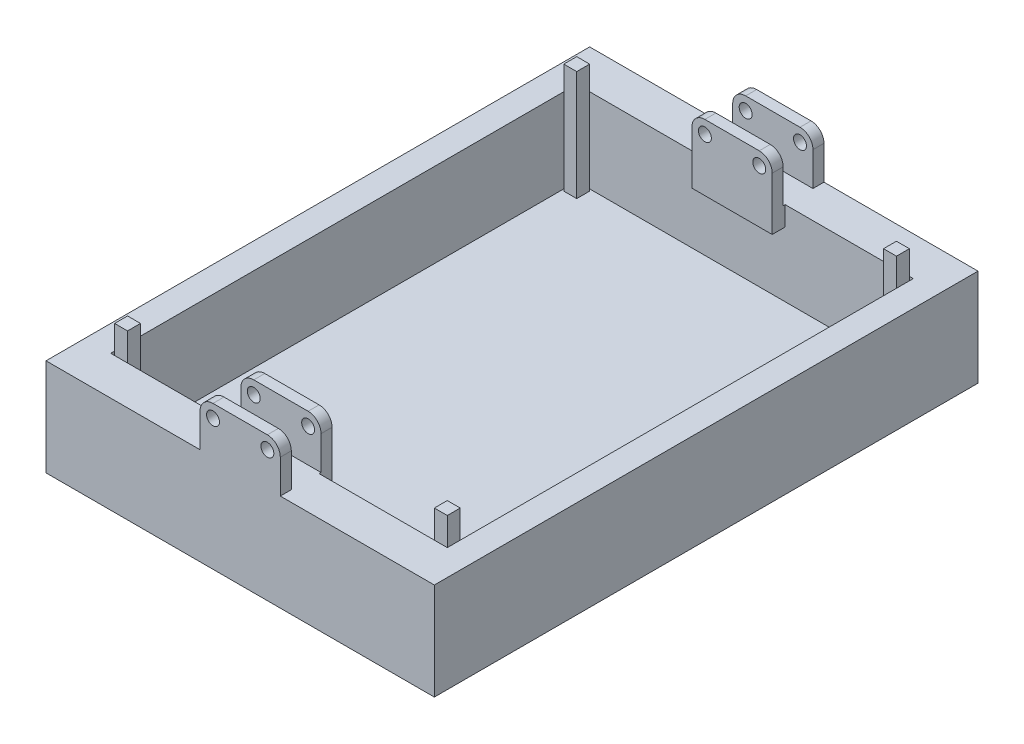
SolidWorks part; units mm, degrees
ref_plane "Front Plane" through (0, 0, 0) normal (0, 0, 1) x (1, 0, 0)
ref_plane "Top Plane" through (0, 0, 0) normal (0, 1, 0) x (1, 0, 0)
ref_plane "Right Plane" through (0, 0, 0) normal (1, 0, 0) x (0, 0, -1)
sketch "Sketch1" plane through (0, 0, 0) normal (0, 1, 0) x (1, 0, 0)
  line L1 (-30, 42) -> (30, 42)
  line L2 (-30, 42) -> (-30, -42)
  line L3 (-30, -42) -> (30, -42)
  line L4 (30, 42) -> (30, -42)
  line L5 (-30, 42) -> (30, -42) construction
  line L6 (-30, -42) -> (30, 42) construction
  point P0 (0, 0)
extrude "Boss-Extrude1" add sketch "Sketch1" along normal blind 9 and the other way blind 6
sketch "Sketch2" plane through (0, 9, 0) normal (0, 1, 0) x (1, 0, 0)
  line L1 (-26, 36) -> (26, 36)
  line L2 (-26, 36) -> (-26, -36)
  line L3 (-26, -36) -> (26, -36)
  line L4 (26, 36) -> (26, -36)
  line L5 (-26, 36) -> (26, -36) construction
  line L6 (-26, -36) -> (26, 36) construction
  point P0 (0, 0)
sketch "Sketch4" plane through (0, 9, 0) normal (0, 1, 0) x (1, 0, 0)
  line L0 (-26, 36) -> (26, 36) construction
  line L1 (-25.7, 35.7) -> (-23.7, 35.7)
  line L2 (-25.7, 35.7) -> (-25.7, 33.7)
  line L3 (-25.7, 33.7) -> (-23.7, 33.7)
  line L4 (-23.7, 35.7) -> (-23.7, 33.7)
  line L5 (-25.7, 35.7) -> (-23.7, 33.7) construction
  line L6 (-25.7, 33.7) -> (-23.7, 35.7) construction
  line L7 (-26, 36) -> (-26, -36) construction
  line L8 (0, -55) -> (0, 55) construction
  line L9 (25.7, 33.7) -> (23.7, 33.7)
  line L10 (23.7, 35.7) -> (23.7, 33.7)
  line L11 (25.7, 35.7) -> (23.7, 35.7)
  line L12 (25.7, 35.7) -> (25.7, 33.7)
  line L13 (-55, 0) -> (55, 0) construction
  line L14 (25.7, -35.7) -> (25.7, -33.7)
  line L15 (25.7, -35.7) -> (23.7, -35.7)
  line L16 (23.7, -35.7) -> (23.7, -33.7)
  line L17 (25.7, -33.7) -> (23.7, -33.7)
  line L18 (-25.7, -33.7) -> (-23.7, -33.7)
  line L19 (-23.7, -35.7) -> (-23.7, -33.7)
  line L20 (-25.7, -35.7) -> (-23.7, -35.7)
  line L21 (-25.7, -35.7) -> (-25.7, -33.7)
  point P0 (-24.7, 34.7)
  dimension "D1" = 0.3
  dimension "D2" = 0.3
extrude "Cut-Extrude2" cut sketch "Sketch2" against normal blind 13
extrude "Boss-Extrude6" add sketch "Sketch4" along normal blind 4 and the other way blind 13
sketch "Sketch7" plane through (0, 0, -42) normal (0, 0, -1) x (-1, 0, 0)
  line L0 (-30, 9) -> (30, 9) construction
  line L1 (0, 10.45) -> (0, -10.45) construction
  line L2 (-6.2, 14.2) -> (-6.2, 9)
  line L3 (-6.2, 9) -> (6.2, 9)
  line L4 (6.2, 9) -> (6.2, 14.2)
  line L5 (-4.2, 16.2) -> (4.2, 16.2)
  circle A0 centre (-4.2, 14.2) radius 1
  circle A1 centre (-4.2, 14.2) radius 2
  circle A2 centre (4.2, 14.2) radius 1
  circle A3 centre (4.2, 14.2) radius 2
  line M5 (30, 9) -> (-30, 9)
  dimension "D1" = 5.2
  dimension "D2" = 4.2
extrude "Boss-Extrude7" add sketch "Sketch7" against normal blind 1.7 contours L4 A3 L5 A1 L2 M5 | A1 A0 | A3 A2
sketch "Sketch8" plane through (0, 0, -36) normal (0, 0, 1) x (1, 0, 0)
  line L1 (-6.2, 9) -> (6.2, 9)
  line L2 (-6.2, 9) -> (-6.2, 6)
  line L3 (-6.2, 6) -> (6.2, 6)
  line L4 (6.2, 9) -> (6.2, 6)
  line L5 (-6.2, 9) -> (6.2, 6) construction
  line L6 (-6.2, 6) -> (6.2, 9) construction
  line L7 (26, 9) -> (-26, 9) construction
  point P0 (0, 7.5)
extrude "Boss-Extrude8" add sketch "Sketch8" along normal blind 2
ref_plane "Plane15" through (0, 0, -38) normal (0, 0, -1) x (-1, 0, 0)
mirror "Mirror2" about plane through (0, 0, -38) normal (0, 0, -1) of "Boss-Extrude7"
mirror "Mirror3" about plane through (0, 0, 0) normal (0, 0, 1) of "Boss-Extrude7", "Boss-Extrude8", "Mirror2"
sketch "Sketch9" plane through (0, -6, 0) normal (0, -1, 0) x (1, 0, 0)
  spline S0 degree 3 poles (0.7137, 34.7755) (1.8785, 34.7254) (2.2488, 34.857) (2.49, 34.5501) knots 56 56 56 56 57 57 57 57
  spline S1 degree 3 poles (-2.0214, 34.749) (-0.9513, 34.8471) (0.7137, 34.7755) (0.7137, 34.7755) knots 55 55 55 55 56 56 56 56
  spline S2 degree 3 poles (-2.4455, 34.5722) (-2.3096, 34.7198) (-2.1092, 34.7409) (-2.0214, 34.749) knots 54 54 54 54 55 55 55 55
  spline S3 degree 3 poles (-2.5869, 34.148) (-2.585, 34.2282) (-2.5802, 34.4261) (-2.4455, 34.5722) knots 53 53 53 53 54 54 54 54
  spline S4 degree 3 poles (-3.0111, 31.6383) (-2.6923, 31.943) (-2.6271, 32.5207) (-2.5869, 34.148) knots 52 52 52 52 53 53 53 53
  spline S5 degree 3 poles (-3.3469, 31.4439) (-3.1748, 31.4999) (-3.0708, 31.5813) (-3.0111, 31.6383) knots 51 51 51 51 52 52 52 52
  spline S6 degree 3 poles (-4.0848, 31.2495) (-3.8538, 31.3104) (-3.5674, 31.3859) (-3.3469, 31.4439) knots 50 50 50 50 51 51 51 51
  spline S7 degree 3 poles (-5.026, 31.002) (-4.7166, 31.0995) (-4.3985, 31.1667) (-4.0848, 31.2495) knots 49 49 49 49 50 50 50 50
  spline S8 degree 3 poles (-5.7912, 30.8076) (-5.5836, 30.7802) (-5.4979, 30.8532) (-5.026, 31.002) knots 48 48 48 48 49 49 49 49
  spline S9 degree 3 poles (-6.3692, 31.1257) (-6.1058, 30.8983) (-5.9496, 30.8285) (-5.7912, 30.8076) knots 47 47 47 47 48 48 48 48
  spline S10 degree 3 poles (-7.7125, 32.6634) (-7.0924, 32.0321) (-6.9176, 31.5992) (-6.3692, 31.1257) knots 46 46 46 46 47 47 47 47
  spline S11 degree 3 poles (-8.225, 32.9462) (-7.9913, 32.9396) (-7.8194, 32.7722) (-7.7125, 32.6634) knots 45 45 45 45 46 46 46 46
  spline S12 degree 3 poles (-8.6669, 32.7694) (-8.6059, 32.8177) (-8.4413, 32.9522) (-8.225, 32.9462) knots 44 44 44 44 45 45 45 45
  spline S13 degree 3 poles (-11.919, 30.5778) (-10.8645, 31.5186) (-9.2962, 32.2723) (-8.6669, 32.7694) knots 43 43 43 43 44 44 44 44
  spline S14 degree 3 poles (-12.1487, 30.2067) (-12.1074, 30.3969) (-11.982, 30.5216) (-11.919, 30.5778) knots 42 42 42 42 43 43 43 43
  spline S15 degree 3 poles (-11.9057, 29.4599) (-12.0986, 29.7866) (-12.1977, 29.9809) (-12.1487, 30.2067) knots 41 41 41 41 42 42 42 42
  spline S16 degree 3 poles (-11.0352, 28.015) (-11.137, 28.1577) (-11.3933, 28.5918) (-11.9057, 29.4599) knots 40 40 40 40 41 41 41 41
  spline S17 degree 3 poles (-10.8408, 27.5378) (-10.8355, 27.7401) (-10.9456, 27.8893) (-11.0352, 28.015) knots 39 39 39 39 40 40 40 40
  spline S18 degree 3 poles (-12.2371, 25.8676) (-12.2021, 25.9015) (-11.8081, 26.2821) (-11.1236, 27.0076) (-11.002, 27.1366) (-10.847, 27.3055) (-10.8408, 27.5378) knots 37 37 37 37 38 38 38 39 39 39 39
  spline S19 degree 3 poles (-13.1915, 25.1518) (-12.9, 25.1661) (-12.7674, 25.355) (-12.2371, 25.8676) knots 36 36 36 36 37 37 37 37
  spline S20 degree 3 poles (-13.6864, 25.2755) (-13.4297, 25.1895) (-13.2992, 25.1466) (-13.1915, 25.1518) knots 35 35 35 35 36 36 36 36
  spline S21 degree 3 poles (-14.6364, 25.6688) (-14.2759, 25.5279) (-14.1426, 25.4285) (-13.6864, 25.2755) knots 34 34 34 34 35 35 35 35
  spline S22 degree 3 poles (-15.7366, 25.8941) (-15.4435, 25.9842) (-15.1745, 25.879) (-14.6364, 25.6688) knots 33 33 33 33 34 34 34 34
  spline S23 degree 3 poles (-16.744, 24.5686) (-16.6335, 24.8681) (-16.5617, 25.1119) (-16.3375, 25.3993) (-16.1902, 25.5882) (-16.0193, 25.8073) (-15.7366, 25.8941) knots 31 31 31 31 32 32 32 33 33 33 33
  spline S24 degree 3 poles (-17.6808, 22.5007) (-17.2185, 23.2827) (-16.9002, 24.1454) (-16.744, 24.5686) knots 30 30 30 30 31 31 31 31
  spline S25 degree 3 poles (-17.8929, 21.829) (-17.9268, 22.1025) (-17.7894, 22.317) (-17.6808, 22.5007) knots 29 29 29 29 30 30 30 30
  spline S26 degree 3 poles (-17.5394, 21.2281) (-17.6276, 21.3114) (-17.8553, 21.5263) (-17.8929, 21.829) knots 28 28 28 28 29 29 29 29
  spline S27 degree 3 poles (-16.9164, 20.8702) (-17.1378, 20.9607) (-17.3359, 21.0361) (-17.5394, 21.2281) knots 27 27 27 27 28 28 28 28
  spline S28 degree 3 poles (-15.4715, 20.0351) (-15.601, 20.3277) (-16.0412, 20.5125) (-16.9164, 20.8702) knots 26 26 26 26 27 27 27 27
  spline S29 degree 3 poles (-15.498, 19.3723) (-15.4392, 19.7228) (-15.3914, 19.8542) (-15.4715, 20.0351) knots 25 25 25 25 26 26 26 26
  spline S30 degree 3 poles (-15.8029, 16.8537) (-15.368, 17.3125) (-15.7504, 17.8671) (-15.498, 19.3723) knots 24 24 24 24 25 25 25 25
  spline S31 degree 3 poles (-16.638, 16.5091) (-16.15, 16.6663) (-15.9061, 16.7449) (-15.8029, 16.8537) knots 23 23 23 23 24 24 24 24
  spline S32 degree 3 poles (-18.7059, 15.7668) (-18.4993, 16.172) (-17.9094, 16.0995) (-16.638, 16.5091) knots 22 22 22 22 23 23 23 23
  spline S33 degree 3 poles (-18.7059, 15.1305) (-18.745, 15.6604) (-18.738, 15.7039) (-18.7059, 15.7668) knots 21 21 21 21 22 22 22 22
  spline S34 degree 3 poles (-18.4805, 13.0361) (-18.5434, 13.5712) (-18.6415, 14.2587) (-18.7059, 15.1305) knots 20 20 20 20 21 21 21 21
  spline S35 degree 3 poles (-18.3878, 12.1524) (-18.4233, 12.5352) (-18.4578, 12.8422) (-18.4805, 13.0361) knots 19 19 19 19 20 20 20 20
  spline S36 degree 3 poles (-17.5526, 12.1347) (-17.9027, 12.1398) (-18.192, 12.147) (-18.3878, 12.1524) knots 18 18 18 18 19 19 19 19
  spline S37 degree 3 poles (-14.8617, 12.148) (-15.9887, 12.1549) (-16.1921, 12.1147) (-17.5526, 12.1347) knots 17 17 17 17 18 18 18 18
  spline S38 degree 3 poles (-12.1311, 12.1214) (-13.3086, 12.088) (-13.6184, 12.1403) (-14.8617, 12.148) knots 16 16 16 16 17 17 17 17
  spline S39 degree 3 poles (-11.4418, 12.148) (-11.6021, 12.1402) (-11.8412, 12.1297) (-12.1311, 12.1214) knots 15 15 15 15 16 16 16 16
  spline S40 degree 3 poles (-11.8394, 14.2821) (-11.7468, 13.4023) (-11.5834, 12.6731) (-11.4418, 12.148) knots 14 14 14 14 15 15 15 15
  spline S41 degree 3 poles (-7.4915, 25.2314) (-9.7211, 23.4524) (-10.7004, 21.3652) (-11.0176, 20.6184) (-12.1869, 17.8646) (-11.9589, 15.4171) (-11.8394, 14.2821) knots 12 12 12 12 13 13 13 14 14 14 14
  spline S42 degree 3 poles (-1.7386, 27.7234) (-4.6519, 27.4552) (-6.7639, 25.812) (-7.4915, 25.2314) knots 11 11 11 11 12 12 12 12
  spline S43 degree 3 poles (3.4842, 27.286) (2.3529, 27.4931) (0.1472, 27.897) (-1.7386, 27.7234) knots 10 10 10 10 11 11 11 11
  spline S44 degree 3 poles (4.1381, 27.1578) (3.9855, 27.1898) (3.759, 27.2357) (3.4842, 27.286) knots 9 9 9 9 10 10 10 10
  spline S45 degree 3 poles (4.6551, 27.5334) (4.543, 27.4478) (4.3649, 27.3145) (4.1381, 27.1578) knots 8 8 8 8 9 9 9 9
  spline S46 degree 3 poles (6.9439, 29.7913) (6.7109, 29.4841) (5.9619, 28.5314) (4.6551, 27.5334) knots 7 7 7 7 8 8 8 8
  spline S47 degree 3 poles (7.2223, 30.1757) (7.1688, 30.0982) (7.0715, 29.9595) (6.9439, 29.7913) knots 6 6 6 6 7 7 7 7
  spline S48 degree 3 poles (5.8835, 30.7722) (6.2402, 30.6401) (6.7011, 30.4489) (7.2223, 30.1757) knots 5 5 5 5 6 6 6 6
  spline S49 degree 3 poles (4.1072, 31.276) (4.5333, 31.183) (5.1362, 31.0491) (5.8835, 30.7722) knots 4 4 4 4 5 5 5 5
  spline S50 degree 3 poles (2.9142, 31.4881) (3.2193, 31.4461) (3.6285, 31.3804) (4.1072, 31.276) knots 3 3 3 3 4 4 4 4
  spline S51 degree 3 poles (2.7419, 32.036) (2.7975, 31.7955) (2.8669, 31.6056) (2.9142, 31.4881) knots 2 2 2 2 3 3 3 3
  spline S52 degree 3 poles (2.6358, 33.4897) (2.6486, 32.8222) (2.6267, 32.5335) (2.7419, 32.036) knots 1 1 1 1 2 2 2 2
  spline S53 degree 3 poles (2.49, 34.5501) (2.6186, 34.3865) (2.6244, 34.0876) (2.6358, 33.4897) knots 0 0 0 0 1 1 1 1
  spline S54 degree 3 poles (-7.6771, 6.3552) (-6.5758, 5.6049) (-6.5386, 4.2823) (-6.5371, 4.1548) knots 21 21 21 21 22 22 22 22
  spline S55 degree 3 poles (-9.639, 6.7529) (-8.6063, 6.9695) (-7.7746, 6.4216) (-7.6771, 6.3552) knots 20 20 20 20 21 21 21 21
  spline S56 degree 3 poles (-10.5404, 6.3552) (-10.1656, 6.6382) (-9.7923, 6.7207) (-9.639, 6.7529) knots 19 19 19 19 20 20 20 20
  spline S57 degree 3 poles (-11.4152, 4.9766) (-11.2241, 5.4914) (-11.0348, 5.9818) (-10.5404, 6.3552) knots 18 18 18 18 19 19 19 19
  spline S58 degree 3 poles (-11.7599, 3.4389) (-11.7395, 3.6641) (-11.6814, 4.2595) (-11.4152, 4.9766) knots 17 17 17 17 18 18 18 18
  spline S59 degree 3 poles (-11.5213, -1.3861) (-12.0603, 0.1233) (-11.9457, 1.3876) (-11.7599, 3.4389) knots 16 16 16 16 17 17 17 17
  spline S60 degree 3 poles (-10.4608, -3.0564) (-10.689, -2.8809) (-11.1298, -2.4825) (-11.5213, -1.3861) knots 15 15 15 15 16 16 16 16
  spline S61 degree 3 poles (-7.2529, -2.5792) (-7.4327, -2.807) (-8.006, -3.5336) (-8.9497, -3.5866) (-9.7154, -3.6295) (-10.2696, -3.2034) (-10.4608, -3.0564) knots 13 13 13 13 14 14 14 15 15 15 15
  spline S62 degree 3 poles (-6.6432, -0.962) (-6.6637, -1.2668) (-6.7538, -1.9466) (-7.2529, -2.5792) knots 12 12 12 12 13 13 13 13
  spline S63 degree 3 poles (-3.2232, -0.8294) (-4.3632, -0.8736) (-5.5032, -0.9178) (-6.6432, -0.962) knots 11 11 11 11 12 12 12 12
  spline S64 degree 3 poles (-5.2381, -5.2568) (-3.3053, -3.6294) (-3.2293, -1.2249) (-3.2232, -0.8294) knots 10 10 10 10 11 11 11 11
  spline S65 degree 3 poles (-9.2678, -6.5824) (-8.6283, -6.58) (-6.8015, -6.5733) (-5.2381, -5.2568) knots 9 9 9 9 10 10 10 10
  spline S66 degree 3 poles (-11.919, -6.0522) (-10.8244, -6.5773) (-9.8106, -6.5844) (-9.2678, -6.5824) knots 8 8 8 8 9 9 9 9
  spline S67 degree 3 poles (-15.2064, -1.7308) (-14.9061, -2.647) (-14.1391, -4.9869) (-11.919, -6.0522) knots 7 7 7 7 8 8 8 8
  spline S68 degree 3 poles (-15.392, 3.3594) (-15.6106, 1.8981) (-15.8567, 0.2532) (-15.2064, -1.7308) knots 6 6 6 6 7 7 7 7
  spline S69 degree 3 poles (-13.5362, 8.105) (-14.8931, 6.6937) (-15.1439, 5.0175) (-15.392, 3.3594) knots 5 5 5 5 6 6 6 6
  spline S70 degree 3 poles (-11.1766, 9.6161) (-11.669, 9.4432) (-12.65, 9.0266) (-13.5362, 8.105) knots 4 4 4 4 5 5 5 5
  spline S71 degree 3 poles (-6.5371, 9.3775) (-8.7176, 10.4412) (-10.8178, 9.7421) (-11.1766, 9.6161) knots 3 3 3 3 4 4 4 4
  spline S72 degree 3 poles (-4.7609, 8.0254) (-4.9182, 8.2088) (-5.5148, 8.8788) (-6.5371, 9.3775) knots 2 2 2 2 3 3 3 3
  spline S73 degree 3 poles (-3.4353, 4.1548) (-3.4229, 4.6986) (-3.4505, 6.4979) (-4.7609, 8.0254) knots 1 1 1 1 2 2 2 2
  spline S74 degree 3 poles (-6.5371, 4.1548) (-5.5032, 4.1548) (-4.4693, 4.1548) (-3.4353, 4.1548) knots 0 0 0 0 1 1 1 1
  spline S75 degree 3 poles (6.0028, -0.1401) (4.8598, -0.1401) (3.7169, -0.1401) (2.574, -0.1401) knots 2 2 2 2 3 3 3 3
  spline S76 degree 3 poles (4.2884, 6.0813) (4.8598, 4.0075) (5.4313, 1.9337) (6.0028, -0.1401) knots 1 1 1 1 2 2 2 2
  spline S77 degree 3 poles (2.574, -0.1401) (3.1454, 1.9337) (3.7169, 4.0075) (4.2884, 6.0813) knots 0 0 0 0 1 1 1 1
  spline S78 degree 3 poles (10.9516, -6.2554) (9.5141, -1.0034) (8.0766, 4.2486) (6.639, 9.5007) knots 7 7 7 7 8 8 8 8
  spline S79 degree 3 poles (7.6288, -6.2554) (8.7364, -6.2554) (9.844, -6.2554) (10.9516, -6.2554) knots 6 6 6 6 7 7 7 7
  spline S80 degree 3 poles (6.6744, -3.0387) (6.9925, -4.1109) (7.3107, -5.1832) (7.6288, -6.2554) knots 5 5 5 5 6 6 6 6
  spline S81 degree 3 poles (1.9023, -3.0387) (3.493, -3.0387) (5.0837, -3.0387) (6.6744, -3.0387) knots 4 4 4 4 5 5 5 5
  spline S82 degree 3 poles (1.1247, -6.2554) (1.3839, -5.1832) (1.6431, -4.1109) (1.9023, -3.0387) knots 3 3 3 3 4 4 4 4
  spline S83 degree 3 poles (-2.1627, -6.2554) (-1.0669, -6.2554) (0.0289, -6.2554) (1.1247, -6.2554) knots 2 2 2 2 3 3 3 3
  spline S84 degree 3 poles (2.1498, 9.5007) (0.7123, 4.2486) (-0.7252, -1.0034) (-2.1627, -6.2554) knots 1 1 1 1 2 2 2 2
  spline S85 degree 3 poles (6.639, 9.5007) (5.1426, 9.5007) (3.6462, 9.5007) (2.1498, 9.5007) knots 0 0 0 0 1 1 1 1
  spline S86 degree 3 poles (12.8958, 9.5007) (12.8958, 4.2486) (12.8958, -1.0034) (12.8958, -6.2554) knots 12 12 12 12 13 13 13 13
  spline S87 degree 3 poles (18.0566, 9.5007) (16.3363, 9.5007) (14.6161, 9.5007) (12.8958, 9.5007) knots 11 11 11 11 12 12 12 12
  spline S88 degree 3 poles (20.5841, -1.554) (19.7416, 2.1309) (18.8991, 5.8158) (18.0566, 9.5007) knots 10 10 10 10 11 11 11 11
  spline S89 degree 3 poles (23.0054, 9.5007) (22.1983, 5.8158) (21.3912, 2.1309) (20.5841, -1.554) knots 9 9 9 9 10 10 10 10
  spline S90 degree 3 poles (28.2724, 9.5007) (26.5167, 9.5007) (24.7611, 9.5007) (23.0054, 9.5007) knots 8 8 8 8 9 9 9 9
  spline S91 degree 3 poles (28.2724, -6.2554) (28.2724, -1.0034) (28.2724, 4.2486) (28.2724, 9.5007) knots 7 7 7 7 8 8 8 8
  spline S92 degree 3 poles (24.9496, -6.2554) (26.0572, -6.2554) (27.1648, -6.2554) (28.2724, -6.2554) knots 6 6 6 6 7 7 7 7
  spline S93 degree 3 poles (24.9496, 5.445) (24.9496, 1.5449) (24.9496, -2.3553) (24.9496, -6.2554) knots 5 5 5 5 6 6 6 6
  spline S94 degree 3 poles (22.0073, -6.2554) (22.9881, -2.3553) (23.9688, 1.5449) (24.9496, 5.445) knots 4 4 4 4 5 5 5 5
  spline S95 degree 3 poles (19.2232, -6.2554) (20.1512, -6.2554) (21.0792, -6.2554) (22.0073, -6.2554) knots 3 3 3 3 4 4 4 4
  spline S96 degree 3 poles (15.9004, 5.445) (17.008, 1.5449) (18.1156, -2.3553) (19.2232, -6.2554) knots 2 2 2 2 3 3 3 3
  spline S97 degree 3 poles (15.9004, -6.2554) (15.9004, -2.3553) (15.9004, 1.5449) (15.9004, 5.445) knots 1 1 1 1 2 2 2 2
  spline S98 degree 3 poles (12.8958, -6.2554) (13.8973, -6.2554) (14.8988, -6.2554) (15.9004, -6.2554) knots 0 0 0 0 1 1 1 1
  spline S99 degree 3 poles (-21.4808, 6.3287) (-20.8444, 5.7775) (-20.7832, 4.995) (-20.7738, 4.8175) knots 31 31 31 31 32 32 32 32
  spline S100 degree 3 poles (-23.1598, 6.8059) (-22.7294, 6.814) (-22.0559, 6.8268) (-21.4808, 6.3287) knots 30 30 30 30 31 31 31 31
  spline S101 degree 3 poles (-24.6798, 6.2933) (-24.2644, 6.785) (-23.6032, 6.7975) (-23.1598, 6.8059) knots 29 29 29 29 30 30 30 30
  spline S102 degree 3 poles (-24.8212, 4.5082) (-25.0312, 4.87) (-25.0208, 5.2313) (-25.0156, 5.3566) (-25.0103, 5.4842) (-24.9859, 5.9311) (-24.6798, 6.2933) knots 27 27 27 27 28 28 28 29 29 29 29
  spline S103 degree 3 poles (-22.5412, 3.2887) (-22.7402, 3.3397) (-23.3066, 3.4787) (-23.9728, 3.8189) (-24.4619, 4.0687) (-24.6768, 4.2594) (-24.8212, 4.5082) knots 25 25 25 25 26 26 26 27 27 27 27
  spline S104 degree 3 poles (-19.625, 2.0869) (-20.9408, 2.8697) (-22.453, 3.2661) (-22.5412, 3.2887) knots 24 24 24 24 25 25 25 25
  spline S105 degree 3 poles (-18.1933, 0.9911) (-18.5912, 1.4718) (-18.9931, 1.711) (-19.625, 2.0869) knots 23 23 23 23 24 24 24 24
  spline S106 degree 3 poles (-17.2743, -2.0666) (-17.2584, -1.6856) (-17.197, -0.213) (-18.1933, 0.9911) knots 22 22 22 22 23 23 23 23
  spline S107 degree 3 poles (-18.1226, -4.647) (-17.3529, -3.5974) (-17.2908, -2.4623) (-17.2743, -2.0666) knots 21 21 21 21 22 22 22 22
  spline S108 degree 3 poles (-22.7887, -6.5826) (-21.8519, -6.5519) (-19.4621, -6.4736) (-18.1226, -4.647) knots 20 20 20 20 21 21 21 21
  spline S109 degree 3 poles (-26.1114, -5.8666) (-24.7507, -6.6303) (-23.4478, -6.6041) (-22.7887, -6.5826) knots 19 19 19 19 20 20 20 20
  spline S110 degree 3 poles (-27.9142, -4.2405) (-27.2783, -5.1994) (-26.4755, -5.6622) (-26.1114, -5.8666) knots 18 18 18 18 19 19 19 19
  spline S111 degree 3 poles (-28.7272, -1.2889) (-28.745, -1.7687) (-28.7263, -3.0161) (-27.9142, -4.2405) knots 17 17 17 17 18 18 18 18
  spline S112 degree 3 poles (-25.3514, -1.2536) (-26.4767, -1.2654) (-27.602, -1.2771) (-28.7272, -1.2889) knots 16 16 16 16 17 17 17 17
  spline S113 degree 3 poles (-24.9096, -2.7559) (-25.3441, -2.1826) (-25.3623, -1.5354) (-25.3514, -1.2536) knots 15 15 15 15 16 16 16 16
  spline S114 degree 3 poles (-22.824, -3.6573) (-23.2815, -3.6316) (-24.2887, -3.575) (-24.9096, -2.7559) knots 14 14 14 14 15 15 15 15
  spline S115 degree 3 poles (-21.357, -3.3391) (-21.8271, -3.7133) (-22.3667, -3.683) (-22.824, -3.6573) knots 13 13 13 13 14 14 14 14
  spline S116 degree 3 poles (-20.7561, -2.208) (-20.766, -2.307) (-20.8375, -2.9256) (-21.357, -3.3391) knots 12 12 12 12 13 13 13 13
  spline S117 degree 3 poles (-21.2333, -0.8294) (-21.1397, -0.9375) (-20.6821, -1.466) (-20.7561, -2.208) knots 11 11 11 11 12 12 12 12
  spline S118 degree 3 poles (-23.3542, 0.0366) (-22.2843, -0.2553) (-21.715, -0.2731) (-21.2333, -0.8294) knots 10 10 10 10 11 11 11 11
  spline S119 degree 3 poles (-26.3058, 1.2385) (-25.2734, 0.5604) (-24.2233, 0.2738) (-23.3542, 0.0366) knots 9 9 9 9 10 10 10 10
  spline S120 degree 3 poles (-28.3207, 3.4478) (-27.9064, 2.283) (-26.9602, 1.6683) (-26.3058, 1.2385) knots 8 8 8 8 9 9 9 9
  spline S121 degree 3 poles (-28.5328, 5.1975) (-28.548, 4.8259) (-28.5752, 4.1632) (-28.3207, 3.4478) knots 7 7 7 7 8 8 8 8
  spline S122 degree 3 poles (-25.97, 9.2273) (-26.3472, 9.0327) (-27.4884, 8.4237) (-28.1086, 7.1064) (-28.48, 6.3175) (-28.5168, 5.5886) (-28.5328, 5.1975) knots 5 5 5 5 6 6 6 7 7 7 7
  spline S123 degree 3 poles (-22.8417, 9.7752) (-23.7999, 9.7933) (-24.8346, 9.8129) (-25.97, 9.2273) knots 4 4 4 4 5 5 5 5
  spline S124 degree 3 poles (-20.5617, 9.3775) (-21.4207, 9.7412) (-22.1433, 9.762) (-22.8417, 9.7752) knots 3 3 3 3 4 4 4 4
  spline S125 degree 3 poles (-18.7326, 8.0519) (-19.4278, 8.8865) (-20.253, 9.2468) (-20.5617, 9.3775) knots 2 2 2 2 3 3 3 3
  spline S126 degree 3 poles (-17.6719, 4.8175) (-17.6567, 5.2662) (-17.6622, 6.7669) (-18.7326, 8.0519) knots 1 1 1 1 2 2 2 2
  spline S127 degree 3 poles (-20.7738, 4.8175) (-19.7398, 4.8175) (-18.7059, 4.8175) (-17.6719, 4.8175) knots 0 0 0 0 1 1 1 1
  spline S128 degree 3 poles (14.4511, -10.7093) (15.1195, -10.765) (15.7159, -11.3032) (15.9888, -12.0702) knots 29 29 29 29 30 30 30 30
  spline S129 degree 3 poles (13.2139, -11.2042) (13.5856, -10.6492) (14.3786, -10.7033) (14.4511, -10.7093) knots 28 28 28 28 29 29 29 29
  spline S130 degree 3 poles (13.0725, -12.0349) (12.9437, -11.6201) (13.1868, -11.2446) (13.2139, -11.2042) knots 27 27 27 27 28 28 28 28
  spline S131 degree 3 poles (13.6204, -12.6358) (13.4118, -12.5097) (13.1666, -12.3378) (13.0725, -12.0349) knots 26 26 26 26 27 27 27 27
  spline S132 degree 3 poles (15.6176, -13.3428) (14.9791, -13.1452) (14.3792, -13.0947) (13.6204, -12.6358) knots 25 25 25 25 26 26 26 26
  spline S133 degree 3 poles (17.5618, -14.4563) (16.9756, -13.7631) (16.1643, -13.512) (15.6176, -13.3428) knots 24 24 24 24 25 25 25 25
  spline S134 degree 3 poles (18.2334, -16.7716) (18.2498, -16.6331) (18.3751, -15.418) (17.5618, -14.4563) knots 23 23 23 23 24 24 24 24
  spline S135 degree 3 poles (17.6855, -18.1679) (18.1278, -17.6004) (18.2058, -17.0039) (18.2334, -16.7716) knots 22 22 22 22 23 23 23 23
  spline S136 degree 3 poles (16.5013, -19.0339) (16.8773, -18.8541) (17.3129, -18.6458) (17.6855, -18.1679) knots 21 21 21 21 22 22 22 22
  spline S137 degree 3 poles (13.0195, -19.2107) (13.2487, -19.2901) (13.8318, -19.471) (14.6102, -19.4581) (15.6285, -19.4412) (16.3566, -19.1031) (16.5013, -19.0339) knots 19 19 19 19 20 20 20 21 21 21 21
  spline S138 degree 3 poles (12.1004, -18.7511) (12.4606, -19.0141) (12.7839, -19.129) (13.0195, -19.2107) knots 18 18 18 18 19 19 19 19
  spline S139 degree 3 poles (11.4288, -18.0795) (11.6844, -18.4388) (12.004, -18.6808) (12.1004, -18.7511) knots 17 17 17 17 18 18 18 18
  spline S140 degree 3 poles (10.9516, -16.047) (10.921, -16.3455) (10.862, -17.2827) (11.4288, -18.0795) knots 16 16 16 16 17 17 17 17
  spline S141 degree 3 poles (12.8958, -16.1177) (12.2477, -16.0941) (11.5996, -16.0705) (10.9516, -16.047) knots 15 15 15 15 16 16 16 16
  spline S142 degree 3 poles (13.1432, -16.8246) (12.9697, -16.5432) (12.9154, -16.2745) (12.8958, -16.1177) knots 14 14 14 14 15 15 15 15
  spline S143 degree 3 poles (16.0418, -16.8777) (15.9133, -17.2268) (15.6053, -17.3795) (15.4055, -17.4786) (14.7487, -17.8043) (14.0994, -17.576) (14.0269, -17.5493) (13.4862, -17.3496) (13.2157, -16.9423) (13.1432, -16.8246) knots 11 11 11 11 12 12 12 13 13 13 14 14 14 14
  spline S144 degree 3 poles (15.9181, -15.9763) (15.9538, -16.0323) (16.2036, -16.4381) (16.0418, -16.8777) knots 10 10 10 10 11 11 11 11
  spline S145 degree 3 poles (15.2995, -15.4991) (15.7274, -15.7122) (15.8568, -15.8803) (15.9181, -15.9763) knots 9 9 9 9 10 10 10 10
  spline S146 degree 3 poles (12.2065, -14.2972) (13.0196, -14.9065) (14.0571, -15.1171) (14.2036, -15.1456) (14.377, -15.1792) (14.8028, -15.2517) (15.2995, -15.4991) knots 7 7 7 7 8 8 8 9 9 9 9
  spline S147 degree 3 poles (11.0223, -12.6712) (11.2782, -13.5869) (11.9366, -14.0951) (12.2065, -14.2972) knots 6 6 6 6 7 7 7 7
  spline S148 degree 3 poles (11.0223, -11.1689) (10.8245, -11.9067) (10.9774, -12.5105) (11.0223, -12.6712) knots 5 5 5 5 6 6 6 6
  spline S149 degree 3 poles (12.1004, -9.5782) (11.8498, -9.7695) (11.2594, -10.2841) (11.0223, -11.1689) knots 4 4 4 4 5 5 5 5
  spline S150 degree 3 poles (17.1199, -9.8786) (16.3066, -8.9931) (15.1616, -8.9724) (14.4511, -8.9596) (13.8764, -8.9492) (12.9462, -8.9324) (12.1004, -9.5782) knots 2 2 2 2 3 3 3 4 4 4 4
  spline S151 degree 3 poles (17.8622, -12.0702) (17.8743, -11.7521) (17.8734, -10.699) (17.1199, -9.8786) knots 1 1 1 1 2 2 2 2
  spline S152 degree 3 poles (15.9888, -12.0702) (16.6132, -12.0702) (17.2377, -12.0702) (17.8622, -12.0702) knots 0 0 0 0 1 1 1 1
  spline S153 degree 3 poles (7.1162, -19.193) (7.1045, -16.5006) (7.0927, -13.8082) (7.0809, -11.1158) knots 7 7 7 7 8 8 8 8
  spline S154 degree 3 poles (4.9423, -19.193) (5.667, -19.193) (6.3916, -19.193) (7.1162, -19.193) knots 6 6 6 6 7 7 7 7
  spline S155 degree 3 poles (4.907, -11.1158) (4.9187, -13.8082) (4.9305, -16.5006) (4.9423, -19.193) knots 5 5 5 5 6 6 6 6
  spline S156 degree 3 poles (2.2381, -11.1158) (3.1278, -11.1158) (4.0174, -11.1158) (4.907, -11.1158) knots 4 4 4 4 5 5 5 5
  spline S157 degree 3 poles (2.2381, -9.2954) (2.2381, -9.9022) (2.2381, -10.509) (2.2381, -11.1158) knots 3 3 3 3 4 4 4 4
  spline S158 degree 3 poles (9.6967, -9.2954) (7.2105, -9.2954) (4.7243, -9.2954) (2.2381, -9.2954) knots 2 2 2 2 3 3 3 3
  spline S159 degree 3 poles (9.6967, -11.1158) (9.6967, -10.509) (9.6967, -9.9022) (9.6967, -9.2954) knots 1 1 1 1 2 2 2 2
  spline S160 degree 3 poles (7.0809, -11.1158) (7.9528, -11.1158) (8.8248, -11.1158) (9.6967, -11.1158) knots 0 0 0 0 1 1 1 1
  spline S161 degree 3 poles (-1.4911, -13.113) (-1.2693, -14.3588) (-1.4418, -15.291) (-1.4868, -15.5167) knots 10 10 10 10 11 11 11 11
  spline S162 degree 3 poles (-2.039, -11.593) (-1.6983, -11.95) (-1.6292, -12.3377) (-1.4911, -13.113) knots 9 9 9 9 10 10 10 10
  spline S163 degree 3 poles (-3.5609, -10.9921) (-3.3513, -10.9991) (-2.5816, -11.0247) (-2.039, -11.593) knots 8 8 8 8 9 9 9 9
  spline S164 degree 3 poles (-4.9553, -11.3986) (-4.4432, -10.9627) (-3.8003, -10.9841) (-3.5609, -10.9921) knots 7 7 7 7 8 8 8 8
  spline S165 degree 3 poles (-5.4855, -12.2293) (-5.267, -11.6838) (-5.0508, -11.4799) (-4.9553, -11.3986) knots 6 6 6 6 7 7 7 7
  spline S166 degree 3 poles (-5.6799, -15.1986) (-5.7944, -14.0227) (-5.8667, -13.181) (-5.4855, -12.2293) knots 5 5 5 5 6 6 6 6
  spline S167 degree 3 poles (-5.3265, -16.5595) (-5.5196, -16.2371) (-5.611, -15.9069) (-5.6799, -15.1986) knots 4 4 4 4 5 5 5 5
  spline S168 degree 3 poles (-4.6018, -17.3018) (-5.0236, -17.0557) (-5.2324, -16.7164) (-5.3265, -16.5595) knots 3 3 3 3 4 4 4 4
  spline S169 degree 3 poles (-3.5609, -17.567) (-3.7552, -17.5649) (-4.1671, -17.5555) (-4.6018, -17.3018) knots 2 2 2 2 3 3 3 3
  spline S170 degree 3 poles (-2.1627, -17.1251) (-2.6912, -17.576) (-3.3764, -17.5689) (-3.5609, -17.567) knots 1 1 1 1 2 2 2 2
  spline S171 degree 3 poles (-1.4868, -15.5167) (-1.6413, -16.2918) (-1.7346, -16.7598) (-2.1627, -17.1251) knots 0 0 0 0 1 1 1 1
  spline S172 degree 3 poles (0.6475, -16.0646) (0.8064, -15.4775) (1.0716, -14.1728) (0.6475, -12.6181) knots 9 9 9 9 10 10 10 10
  spline S173 degree 3 poles (-0.5721, -18.4153) (0.214, -17.6656) (0.4483, -16.8002) (0.6475, -16.0646) knots 8 8 8 8 9 9 9 9
  spline S174 degree 3 poles (-6.8641, -18.0088) (-5.6359, -19.4611) (-3.8182, -19.5246) (-3.5944, -19.5288) (-3.1459, -19.5373) (-1.7049, -19.4958) (-0.5721, -18.4153) knots 6 6 6 6 7 7 7 8 8 8 8
  spline S175 degree 3 poles (-7.6948, -12.2647) (-8.1567, -13.6589) (-7.9772, -14.8387) (-7.8892, -15.3753) (-7.7524, -16.2097) (-7.6, -17.1387) (-6.8641, -18.0088) knots 4 4 4 4 5 5 5 6 6 6 6
  spline S176 degree 3 poles (-6.1748, -9.8786) (-7.1458, -10.6074) (-7.4696, -11.5848) (-7.6948, -12.2647) knots 3 3 3 3 4 4 4 4
  spline S177 degree 3 poles (-0.7842, -10.0377) (-1.8185, -9.1725) (-3.0009, -9.1156) (-3.4353, -9.101) (-3.8909, -9.0856) (-5.0875, -9.0626) (-6.1748, -9.8786) knots 1 1 1 1 2 2 2 3 3 3 3
  spline S178 degree 3 poles (0.6475, -12.6181) (0.4323, -11.8295) (0.1586, -10.8263) (-0.7842, -10.0377) knots 0 0 0 0 1 1 1 1
  spline S179 degree 3 poles (-12.078, -16.206) (-12.0793, -16.7791) (-12.4963, -17.2942) (-13.0855, -17.4256) knots 4 4 4 4 5 5 5 5
  spline S180 degree 3 poles (-12.891, -15.0395) (-12.4002, -15.2329) (-12.0769, -15.6999) (-12.078, -16.206) knots 3 3 3 3 4 4 4 4
  spline S181 degree 3 poles (-15.1887, -15.0395) (-14.4228, -15.0395) (-13.6569, -15.0395) (-12.891, -15.0395) knots 2 2 2 2 3 3 3 3
  spline S182 degree 3 poles (-15.1887, -17.4256) (-15.1887, -16.6302) (-15.1887, -15.8349) (-15.1887, -15.0395) knots 1 1 1 1 2 2 2 2
  spline S183 degree 3 poles (-13.0855, -17.4256) (-13.7865, -17.4256) (-14.4876, -17.4256) (-15.1887, -17.4256) knots 0 0 0 0 1 1 1 1
  spline S184 degree 3 poles (-15.1887, -13.2191) (-15.1887, -12.4944) (-15.1887, -11.7698) (-15.1887, -11.0451) knots 4 4 4 4 5 5 5 5
  spline S185 degree 3 poles (-13.2799, -13.2191) (-13.9162, -13.2191) (-14.5524, -13.2191) (-15.1887, -13.2191) knots 3 3 3 3 4 4 4 4
  spline S186 degree 3 poles (-12.3608, -12.1321) (-12.3725, -12.6509) (-12.7527, -13.1071) (-13.2799, -13.2191) knots 2 2 2 2 3 3 3 3
  spline S187 degree 3 poles (-13.1031, -11.0451) (-12.6474, -11.2209) (-12.3501, -11.6593) (-12.3608, -12.1321) knots 1 1 1 1 2 2 2 2
  spline S188 degree 3 poles (-15.1887, -11.0451) (-14.4935, -11.0451) (-13.7983, -11.0451) (-13.1031, -11.0451) knots 0 0 0 0 1 1 1 1
  spline S189 degree 3 poles (-9.8511, -16.6125) (-9.8261, -16.0491) (-9.9633, -15.635) (-9.9917, -15.5521) knots 9 9 9 9 10 10 10 10
  spline S190 degree 3 poles (-10.5757, -18.4683) (-9.9033, -17.7892) (-9.8651, -16.9279) (-9.8511, -16.6125) knots 8 8 8 8 9 9 9 9
  spline S191 degree 3 poles (-12.1487, -19.193) (-11.9013, -19.1695) (-11.1678, -19.0664) (-10.5757, -18.4683) knots 7 7 7 7 8 8 8 8
  spline S192 degree 3 poles (-17.3626, -19.193) (-15.6247, -19.193) (-13.8867, -19.193) (-12.1487, -19.193) knots 6 6 6 6 7 7 7 7
  spline S193 degree 3 poles (-17.3626, -9.2954) (-17.3626, -12.5946) (-17.3626, -15.8938) (-17.3626, -19.193) knots 5 5 5 5 6 6 6 6
  spline S194 degree 3 poles (-12.4845, -9.2954) (-14.1106, -9.2954) (-15.7366, -9.2954) (-17.3626, -9.2954) knots 4 4 4 4 5 5 5 5
  spline S195 degree 3 poles (-10.5227, -10.2498) (-11.2398, -9.3433) (-12.3255, -9.2992) (-12.4845, -9.2954) knots 3 3 3 3 4 4 4 4
  spline S196 degree 3 poles (-9.9925, -11.8582) (-9.9869, -11.6326) (-10.0001, -10.9104) (-10.5227, -10.2498) knots 2 2 2 2 3 3 3 3
  spline S197 degree 3 poles (-11.2473, -14.0321) (-11.1284, -13.9527) (-10.0255, -13.1903) (-9.9925, -11.8582) knots 1 1 1 1 2 2 2 2
  spline S198 degree 3 poles (-9.9917, -15.5521) (-10.2979, -14.658) (-10.9909, -14.1882) (-11.2473, -14.0321) knots 0 0 0 0 1 1 1 1
  spline S199 degree 3 poles (20.6769, 19.306) (20.6799, 18.6366) (20.0643, 18.1346) (19.4441, 18.113) knots 3 3 3 3 4 4 4 4
  spline S200 degree 3 poles (19.4971, 20.4858) (20.0859, 20.4429) (20.6739, 19.9578) (20.6769, 19.306) knots 2 2 2 2 3 3 3 3
  spline S201 degree 3 poles (18.1185, 19.2992) (18.1174, 20.0042) (18.8215, 20.535) (19.4971, 20.4858) knots 1 1 1 1 2 2 2 2
  spline S202 degree 3 poles (19.4441, 18.113) (18.7805, 18.0899) (18.1195, 18.617) (18.1185, 19.2992) knots 0 0 0 0 1 1 1 1
  spline S203 degree 3 poles (17.9482, 21.497) (17.9005, 21.4915) (17.7878, 21.4854) (17.6678, 21.5463) knots 11 11 11 11 12 12 12 12
  spline S204 degree 3 poles (18.7283, 21.8202) (18.5075, 21.5993) (18.0632, 21.5165) (17.9482, 21.497) knots 10 10 10 10 11 11 11 11
  spline S205 degree 3 poles (18.8255, 21.9704) (18.8166, 21.9417) (18.795, 21.887) (18.7283, 21.8202) knots 9 9 9 9 10 10 10 10
  spline S206 degree 3 poles (18.7459, 22.3504) (18.7725, 22.3053) (18.8775, 22.1382) (18.8255, 21.9704) knots 8 8 8 8 9 9 9 9
  spline S207 degree 3 poles (17.2083, 25.7351) (18.0176, 23.9013) (18.6039, 22.5915) (18.7459, 22.3504) knots 7 7 7 7 8 8 8 8
  spline S208 degree 3 poles (16.5366, 26.1239) (16.6976, 26.1576) (16.8042, 26.1732) (16.9167, 26.1239) (17.1212, 26.0343) (17.1909, 25.8011) (17.2083, 25.7351) knots 5 5 5 5 6 6 6 7 7 7 7
  spline S209 degree 3 poles (15.7413, 25.903) (16.0647, 26.0147) (16.3368, 26.082) (16.5366, 26.1239) knots 4 4 4 4 5 5 5 5
  spline S210 degree 3 poles (15.5646, 25.7439) (15.6159, 25.8474) (15.7107, 25.8905) (15.7413, 25.903) knots 3 3 3 3 4 4 4 4
  spline S211 degree 3 poles (15.6176, 25.3639) (15.5272, 25.4779) (15.5062, 25.6263) (15.5646, 25.7439) knots 2 2 2 2 3 3 3 3
  spline S212 degree 3 poles (17.4204, 21.8379) (16.8194, 23.0132) (16.2185, 24.1886) (15.6176, 25.3639) knots 1 1 1 1 2 2 2 2
  spline S213 degree 3 poles (17.6678, 21.5463) (17.492, 21.6355) (17.4324, 21.8017) (17.4204, 21.8379) knots 0 0 0 0 1 1 1 1
  spline S214 degree 3 poles (14.6808, 27.476) (13.7804, 27.495) (13.0718, 28.2711) (13.0725, 29.1462) knots 3 3 3 3 4 4 4 4
  spline S215 degree 3 poles (16.3599, 29.1462) (16.3584, 28.2449) (15.6065, 27.4564) (14.6808, 27.476) knots 2 2 2 2 3 3 3 3
  spline S216 degree 3 poles (14.7957, 30.8164) (15.6713, 30.775) (16.3613, 30.0112) (16.3599, 29.1462) knots 1 1 1 1 2 2 2 2
  spline S217 degree 3 poles (13.0725, 29.1462) (13.0732, 30.0699) (13.864, 30.8605) (14.7957, 30.8164) knots 0 0 0 0 1 1 1 1
  spline S218 degree 3 poles (3.4842, 17.2514) (3.4835, 15.7587) (2.2905, 14.4508) (0.78, 14.3882) knots 3 3 3 3 4 4 4 4
  spline S219 degree 3 poles (0.9391, 20.1014) (2.3579, 19.966) (3.4849, 18.7031) (3.4842, 17.2514) knots 2 2 2 2 3 3 3 3
  spline S220 degree 3 poles (0.78, 14.3882) (-0.816, 14.322) (-2.1612, 15.6712) (-2.1627, 17.2448) (-2.1644, 18.9021) (-0.6751, 20.2554) (0.9391, 20.1014) knots 0 0 0 0 1 1 1 2 2 2 2
  spline S221 degree 3 poles (21.6622, 18.0998) (21.7462, 18.2496) (22.2987, 19.2753) (21.8036, 20.3444) knots 52 52 52 52 53 53 53 53
  spline S222 degree 3 poles (20.8624, 17.1984) (20.964, 17.2755) (21.3852, 17.6056) (21.6622, 18.0998) knots 51 51 51 51 52 52 52 52
  spline S223 degree 3 poles (19.9853, 16.6311) (20.1087, 16.8742) (20.3631, 16.8193) (20.8624, 17.1984) knots 50 50 50 50 51 51 51 51
  spline S224 degree 3 poles (20.8315, 14.671) (20.6623, 15.6454) (19.7333, 16.1347) (19.9853, 16.6311) knots 49 49 49 49 50 50 50 50
  spline S225 degree 3 poles (17.7739, 11.1361) (17.8451, 11.0958) (18.0561, 11.0141) (18.5869, 11.3659) (18.9986, 11.6387) (21.1145, 13.0417) (20.8315, 14.671) knots 47 47 47 47 48 48 48 49 49 49 49
  spline S226 degree 3 poles (17.5441, 11.6133) (17.548, 11.4512) (17.6146, 11.2261) (17.7739, 11.1361) knots 46 46 46 46 47 47 47 47
  spline S227 degree 3 poles (19.0818, 13.8756) (18.4478, 13.0886) (17.974, 12.4608) (17.7208, 12.1063) (17.6608, 12.0223) (17.5385, 11.8462) (17.5441, 11.6133) knots 44 44 44 44 45 45 45 46 46 46 46
  spline S228 degree 3 poles (18.1627, 16.5091) (18.469, 15.6313) (18.7754, 14.7534) (19.0818, 13.8756) knots 43 43 43 43 44 44 44 44
  spline S229 degree 3 poles (15.6706, 15.6784) (16.5013, 15.9553) (17.332, 16.2322) (18.1627, 16.5091) knots 42 42 42 42 43 43 43 43
  spline S230 degree 3 poles (15.0874, 13.204) (15.3753, 14.1689) (15.5831, 15.2156) (15.6706, 15.6784) knots 41 41 41 41 42 42 42 42
  spline S231 degree 3 poles (14.5925, 12.4793) (14.9053, 12.6124) (15.0218, 12.9841) (15.0874, 13.204) knots 40 40 40 40 41 41 41 41
  spline S232 degree 3 poles (14.0623, 12.4793) (14.1526, 12.4365) (14.3832, 12.3903) (14.5925, 12.4793) knots 39 39 39 39 40 40 40 40
  spline S233 degree 3 poles (14.345, 16.6505) (13.4674, 13.0512) (13.8691, 12.571) (14.0623, 12.4793) knots 38 38 38 38 39 39 39 39
  spline S234 degree 3 poles (16.9962, 17.8877) (16.1125, 17.4753) (15.2288, 17.0629) (14.345, 16.6505) knots 37 37 37 37 38 38 38 38
  spline S235 degree 3 poles (17.0669, 18.4533) (17.092, 18.2157) (17.0406, 18.0152) (16.9962, 17.8877) knots 36 36 36 36 37 37 37 37
  spline S236 degree 3 poles (16.7487, 19.3546) (16.8063, 19.0007) (17.0249, 18.8505) (17.0669, 18.4533) knots 35 35 35 35 36 36 36 36
  spline S237 degree 3 poles (16.9078, 20.15) (16.7249, 19.7955) (16.7202, 19.5301) (16.7487, 19.3546) knots 34 34 34 34 35 35 35 35
  spline S238 degree 3 poles (15.5469, 22.7128) (16.0005, 21.8585) (16.4542, 21.0042) (16.9078, 20.15) knots 33 33 33 33 34 34 34 34
  spline S239 degree 3 poles (14.0092, 25.8411) (14.5218, 24.7983) (15.0343, 23.7555) (15.5469, 22.7128) knots 32 32 32 32 33 33 33 33
  spline S240 degree 3 poles (13.7795, 26.1062) (13.8561, 26.0179) (13.9326, 25.9295) (14.0092, 25.8411) knots 31 31 31 31 32 32 32 32
  spline S241 degree 3 poles (13.532, 25.9472) (13.6145, 26.0002) (13.697, 26.0532) (13.7795, 26.1062) knots 30 30 30 30 31 31 31 31
  spline S242 degree 3 poles (11.0119, 23.3234) (11.852, 24.198) (12.692, 25.0726) (13.532, 25.9472) knots 29 29 29 29 30 30 30 30
  spline S243 degree 3 poles (8.866, 21.2635) (9.5813, 21.9501) (10.2966, 22.6368) (11.0119, 23.3234) knots 28 28 28 28 29 29 29 29
  spline S244 degree 3 poles (7.0279, 19.4253) (7.6406, 20.0381) (8.2533, 20.6508) (8.866, 21.2635) knots 27 27 27 27 28 28 28 28
  spline S245 degree 3 poles (6.2546, 18.5902) (6.5392, 18.874) (6.7963, 19.1543) (7.0279, 19.4253) knots 26 26 26 26 27 27 27 27
  spline S246 degree 3 poles (5.7377, 18.0998) (5.9073, 18.2529) (6.0801, 18.4162) (6.2546, 18.5902) knots 25 25 25 25 26 26 26 26
  spline S247 degree 3 poles (5.5167, 17.7463) (5.5904, 17.8641) (5.664, 17.9819) (5.7377, 18.0998) knots 24 24 24 24 25 25 25 25
  spline S248 degree 3 poles (5.4549, 13.3631) (5.4755, 14.8241) (5.4961, 16.2852) (5.5167, 17.7463) knots 23 23 23 23 24 24 24 24
  spline S249 degree 3 poles (5.9851, 13.257) (5.8084, 13.2924) (5.6316, 13.3277) (5.4549, 13.3631) knots 22 22 22 22 23 23 23 23
  spline S250 degree 3 poles (6.0381, 12.6031) (6.0277, 12.8335) (6.0091, 13.0519) (5.9851, 13.257) knots 21 21 21 21 22 22 22 22
  spline S251 degree 3 poles (6.0474, 12.1597) (6.0479, 12.302) (6.045, 12.4499) (6.0381, 12.6031) knots 20 20 20 20 21 21 21 21
  spline S252 degree 3 poles (2.7154, 12.1612) (4.1352, 12.1525) (5.2911, 12.1557) (6.0474, 12.1597) knots 19 19 19 19 20 20 20 20
  spline S253 degree 3 poles (0.8065, 12.1789) (1.1579, 12.175) (1.7925, 12.1668) (2.7154, 12.1612) knots 18 18 18 18 19 19 19 19
  spline S254 degree 3 poles (-4.7609, 12.1612) (-2.2275, 12.1985) (-0.408, 12.1923) (0.8065, 12.1789) knots 17 17 17 17 18 18 18 18
  spline S255 degree 3 poles (-4.7609, 13.3012) (-4.7609, 12.9212) (-4.7609, 12.5412) (-4.7609, 12.1612) knots 16 16 16 16 17 17 17 17
  spline S256 degree 3 poles (-3.9125, 13.3012) (-4.1953, 13.3012) (-4.4781, 13.3012) (-4.7609, 13.3012) knots 15 15 15 15 16 16 16 16
  spline S257 degree 3 poles (-4.0009, 15.3249) (-3.9906, 15.0884) (-3.9229, 13.5382) (-3.9125, 13.3012) knots 14 14 14 14 15 15 15 15
  spline S258 degree 3 poles (-2.5074, 20.7509) (-3.8836, 19.4827) (-4.0392, 17.7676) (-4.0716, 17.4105) (-4.0847, 17.2654) (-4.0831, 17.2128) (-4.0009, 15.3249) knots 12 12 12 12 13 13 13 14 14 14 14
  spline S259 degree 3 poles (-0.0324, 21.9439) (-0.5917, 21.8466) (-1.6091, 21.5787) (-2.5074, 20.7509) knots 11 11 11 11 12 12 12 12
  spline S260 degree 3 poles (2.9805, 21.9439) (1.9762, 21.9439) (0.9719, 21.9439) (-0.0324, 21.9439) knots 10 10 10 10 11 11 11 11
  spline S261 degree 3 poles (3.5284, 22.3946) (3.3457, 22.2444) (3.1631, 22.0942) (2.9805, 21.9439) knots 9 9 9 9 10 10 10 10
  spline S262 degree 3 poles (8.4286, 27.0076) (6.7952, 25.47) (5.1618, 23.9323) (3.5284, 22.3946) knots 8 8 8 8 9 9 9 9
  spline S263 degree 3 poles (11.6762, 30.242) (10.5937, 29.1639) (9.5111, 28.0858) (8.4286, 27.0076) knots 7 7 7 7 8 8 8 8
  spline S264 degree 3 poles (12.5776, 31.4615) (12.0614, 31.0196) (11.7996, 30.5236) (11.6762, 30.242) knots 6 6 6 6 7 7 7 7
  spline S265 degree 3 poles (14.2478, 32.2304) (14.0952, 32.2095) (13.3127, 32.0908) (12.5776, 31.4615) knots 5 5 5 5 6 6 6 6
  spline S266 degree 3 poles (16.4748, 31.7001) (15.5467, 32.3587) (14.5633, 32.2735) (14.2478, 32.2304) knots 4 4 4 4 5 5 5 5
  spline S267 degree 3 poles (17.6969, 29.8474) (17.6461, 30.0783) (17.4074, 31.0384) (16.4748, 31.7001) knots 3 3 3 3 4 4 4 4
  spline S268 degree 3 poles (17.7208, 28.015) (17.7129, 28.6258) (17.7049, 29.2366) (17.6969, 29.8474) knots 2 2 2 2 3 3 3 3
  spline S269 degree 3 poles (20.5134, 21.5463) (19.5825, 23.7025) (18.6517, 25.8588) (17.7208, 28.015) knots 1 1 1 1 2 2 2 2
  spline S270 degree 3 poles (21.8036, 20.3444) (21.4342, 21.1421) (20.7126, 21.4649) (20.5134, 21.5463) knots 0 0 0 0 1 1 1 1
extrude "Cut-Extrude4" cut sketch "Sketch9" against normal blind 1
